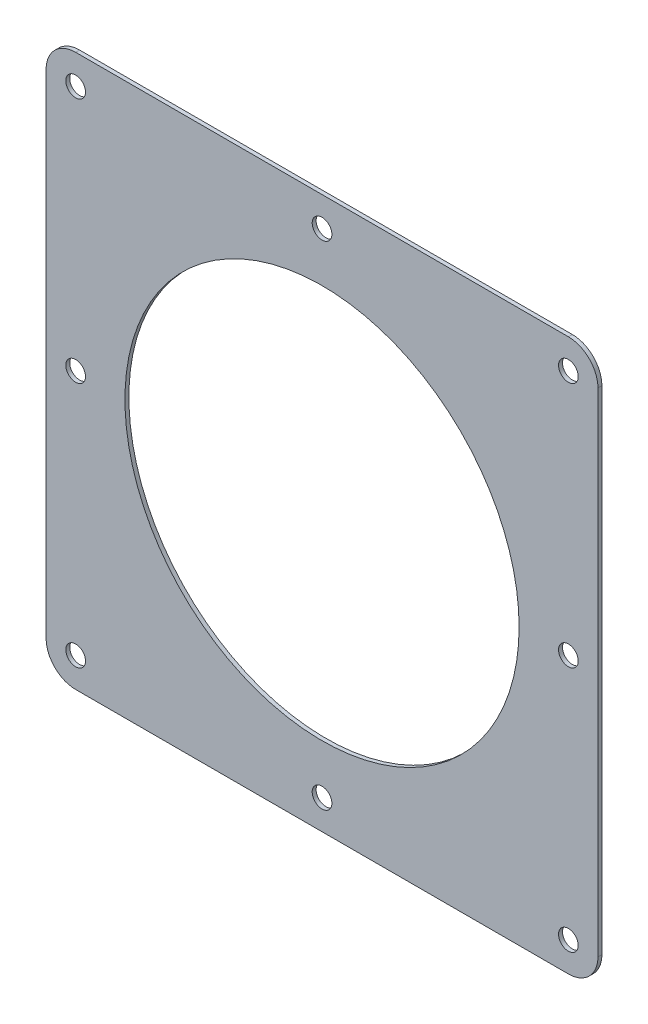
SolidWorks part; units mm, degrees
ref_plane "Front Plane" through (0, 0, 0) normal (0, 0, 1) x (1, 0, 0)
ref_plane "Top Plane" through (0, 0, 0) normal (0, 1, 0) x (1, 0, 0)
ref_plane "Right Plane" through (0, 0, 0) normal (1, 0, 0) x (0, 0, -1)
sketch "Sketch2" plane through (0, 0, 0) normal (0, 0, 1) x (1, 0, 0)
  line L0 (-125, 125) -> (125, 125) construction
  line L1 (-125, 140) -> (125, 140)
  line L2 (-140, 125) -> (-140, -125)
  line L3 (-125, -140) -> (125, -140)
  line L4 (140, 125) -> (140, -125)
  line L5 (-140, 140) -> (140, -140) construction
  line L6 (-140, -140) -> (140, 140) construction
  line L7 (125, 125) -> (125, -125) construction
  line L8 (125, -125) -> (-125, -125) construction
  line L9 (-125, -125) -> (-125, 125) construction
  arc A0 (-140, -125) -> (-125, -140) centre (-125, -125) ccw
  arc A1 (125, -140) -> (140, -125) centre (125, -125) ccw
  arc A2 (125, 140) -> (140, 125) centre (125, 125) cw
  arc A3 (-125, 140) -> (-140, 125) centre (-125, 125) ccw
  circle A4 centre (-125, 125) radius 5
  circle A5 centre (0, 125) radius 5
  circle A6 centre (125, 125) radius 5
  circle A13 centre (0, 0) radius 4
  circle A14 centre (125, 0) radius 5
  circle A15 centre (-125, 0) radius 5
  circle A16 centre (-125, -125) radius 5
  circle A17 centre (0, -125) radius 5
  circle A18 centre (125, -125) radius 5
  point P0 (0, 0)
  dimension "D3" = 15
  dimension "D4" = 10
  dimension "D5" = 10
  dimension "D6" = 10
  dimension "D7" = 8
  dimension "D8" = 10
  dimension "D9" = 10
  dimension "D10" = 10
  dimension "D11" = 10
  dimension "D1" = 280
  dimension "D2" = 280
extrude "Boss-Extrude1" add sketch "Sketch2" along normal blind 2
sketch "Sketch7" plane through (0, 0, 2) normal (0, 0, 1) x (1, 0, 0)
  circle A0 centre (0, 0) radius 100
  dimension "D1" = 200
extrude "Cut-Extrude2" cut sketch "Sketch7" against normal blind 10
